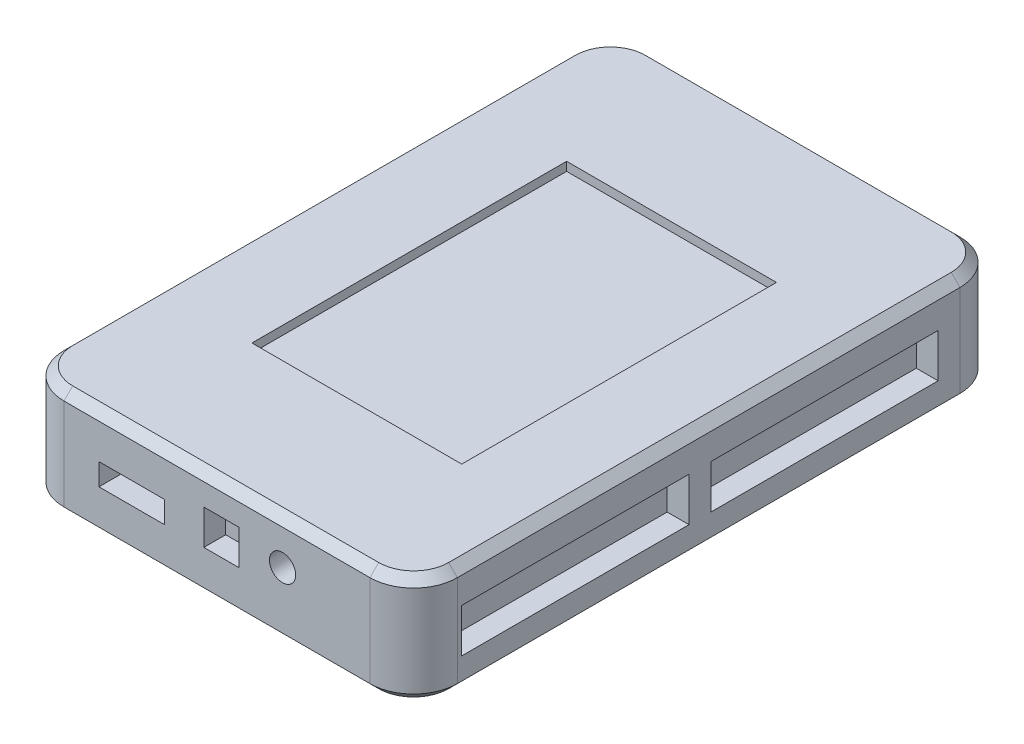
SolidWorks part; units mm, degrees
ref_plane "Front Plane" through (0, 0, 0) normal (0, 0, 1) x (1, 0, 0)
ref_plane "Top Plane" through (0, 0, 0) normal (0, 1, 0) x (1, 0, 0)
ref_plane "Right Plane" through (0, 0, 0) normal (1, 0, 0) x (0, 0, -1)
sketch "Esquisse1" plane through (0, 0, 0) normal (0, 1, 0) x (1, 0, 0)
  line L1 (0, 0) -> (90, 0)
  line L2 (0, 0) -> (0, 135)
  line L3 (0, 135) -> (90, 135)
  line L4 (90, 0) -> (90, 135)
  dimension "D1" = 90
  dimension "D2" = 135
extrude "Boss.-Extru.1" add sketch "Esquisse1" along normal blind 25 contours L3 L4 L1 L2
fillet "Congé1" radius 10 1 edges at (90, 12.5, 0)
fillet "Congé2" radius 10 1 edges at (90, 12.5, -135)
fillet "Congé3" radius 10 1 edges at (0, 12.5, -135)
fillet "Congé4" radius 10 1 edges at (0, 12.5, 0)
chamfer "Chanfrein1" distance 2 angle 45 8 edges at (45, 25, 0) (2.9289, 25, -2.9289) (87.0711, 25, -2.9289) (0, 25, -67.5) (90, 25, -67.5) (2.9289, 25, -132.0711) (87.0711, 25, -132.0711) (45, 25, -135)
chamfer "Chanfrein2" distance 2 angle 45 8 edges at (87.0711, 0, -2.9289) (90, 0, -67.5) (87.0711, 0, -132.0711) (45, 0, -135) (2.9289, 0, -132.0711) (0, 0, -67.5) (2.9289, 0, -2.9289) (45, 0, 0)
ref_plane "Plan1" through (0, 0, 0) normal (0, 0, 1) x (1, 0, 0)
sketch "Esquisse2" plane through (0, 0, 0) normal (0, 0, 1) x (1, 0, 0)
  line L1 (42, 18) -> (50, 18)
  line L2 (42, 18) -> (42, 10)
  line L3 (42, 10) -> (50, 10)
  line L4 (50, 18) -> (50, 10)
  line L5 (18, 15) -> (33, 15)
  line L6 (18, 15) -> (18, 10)
  line L7 (18, 10) -> (33, 10)
  line L8 (33, 15) -> (33, 10)
  line L9 (10, 25) -> (80, 25) construction
  line L10 (0, 2) -> (0, 23) construction
  line L11 (90, 23) -> (90, 2) construction
  circle A0 centre (60, 15) radius 3
  dimension "D1" = 6
  dimension "D4" = 10
  dimension "D5" = 15
  dimension "D9" = 30
  dimension "D2" = 8
  dimension "D3" = 8
  dimension "D6" = 5
  dimension "D7" = 10
  dimension "D8" = 18
  dimension "D10" = 7
  dimension "D11" = 40
extrude "Enlèv. mat.-Extru.1" cut sketch "Esquisse2" against normal blind 5
ref_plane "Plan2" through (0, 0, 0) normal (-1, 0, 0) x (0, 0, 1)
sketch "Esquisse3" plane through (0, 0, 0) normal (-1, 0, 0) x (0, 0, 1)
  line L0 (-125, 25) -> (-10, 25) construction
  line L1 (-90, 17) -> (-15, 17)
  line L2 (-90, 17) -> (-90, 9)
  line L3 (-90, 9) -> (-15, 9)
  line L4 (-15, 17) -> (-15, 9)
  line L5 (0, -11.55) -> (0, 11.55) construction
  line L6 (-135, 2) -> (-135, 23) construction
  circle A0 centre (-112, 17) radius 2
  circle A1 centre (-100, 17) radius 2
  point P10 (-67.5, 25)
  dimension "D1" = 4
  dimension "D2" = 4
  dimension "D5" = 8
  dimension "D6" = 8
  dimension "D9" = 23
  dimension "D10" = 35
  dimension "D3" = 75
  dimension "D4" = 8
  dimension "D7" = 8
  dimension "D8" = 15
extrude "Enlèv. mat.-Extru.2" cut sketch "Esquisse3" against normal blind 5
ref_plane "Plan3" through (0, 25, 0) normal (0, 1, 0) x (1, 0, 0)
sketch "Esquisse4" plane through (0, 25, 0) normal (0, 1, 0) x (1, 0, 0)
  line L0 (10, 135) -> (80, 135) construction
  line L1 (70, 31) -> (22, 31)
  line L2 (70, 31) -> (70, 103)
  line L3 (70, 103) -> (22, 103)
  line L4 (22, 31) -> (22, 103)
  line L5 (0, 10) -> (0, 125) construction
  dimension "D1" = 48
  dimension "D2" = 72
  dimension "D3" = 32
  dimension "D4" = 22
extrude "Enlèv. mat.-Extru.3" cut sketch "Esquisse4" against normal blind 2 contours L1 L4 L3 L2
ref_plane "Plan4" through (0, 0, -135) normal (0, 0, -1) x (-1, 0, 0)
sketch "Esquisse5" plane through (0, 0, -135) normal (0, 0, -1) x (-1, 0, 0)
  line L0 (-30, 20) -> (-20, 20)
  line L1 (-30, 10) -> (-20, 10)
  line L2 (-80, 25) -> (-10, 25) construction
  line L3 (0, 23) -> (0, 2) construction
  arc A0 (-20, 20) -> (-20, 10) centre (-20, 15) cw
  arc A1 (-30, 10) -> (-30, 20) centre (-30, 15) cw
  point P8 (-35, 15)
  point P9 (-15, 15)
  dimension "D1" = 10
  dimension "D2" = 5
  dimension "D3" = 20
  dimension "D4" = 15
extrude "Enlèv. mat.-Extru.4" cut sketch "Esquisse5" against normal blind 2
ref_plane "Plan5" through (0, 0, -133) normal (0, 0, -1) x (-1, 0, 0)
sketch "Esquisse6" plane through (0, 0, -133) normal (0, 0, -1) x (-1, 0, 0)
  line L0 (-20, 20) -> (-30, 20) construction
  circle A0 centre (-30, 15) radius 1.5
  circle A1 centre (-20, 15) radius 1.5
  arc A2 (-20, 10) -> (-20, 20) centre (-20, 15) ccw construction
  point P8 (-15, 15)
  dimension "D1" = 3
  dimension "D2" = 3
  dimension "D3" = 5
  dimension "D4" = 5
extrude "Boss.-Extru.2" add sketch "Esquisse6" along normal blind 2
ref_plane "Plan6" through (90, 0, 0) normal (1, 0, 0) x (0, 0, -1)
sketch "Esquisse7" plane through (90, 0, 0) normal (1, 0, 0) x (0, 0, -1)
  line L0 (10, 25) -> (125, 25) construction
  line L1 (11, 17) -> (63, 17)
  line L2 (11, 17) -> (11, 7)
  line L3 (11, 7) -> (63, 7)
  line L4 (63, 17) -> (63, 7)
  line L5 (68, 17) -> (120, 17)
  line L6 (68, 17) -> (68, 7)
  line L7 (68, 7) -> (120, 7)
  line L8 (120, 17) -> (120, 7)
  line L9 (0, 2) -> (0, 23) construction
  line L10 (135, 23) -> (135, 2) construction
  point P12 (0, 12.5)
  dimension "D1" = 52
  dimension "D2" = 10
  dimension "D3" = 52
  dimension "D4" = 10
  dimension "D5" = 8
  dimension "D6" = 11
  dimension "D7" = 15
  dimension "D8" = 8
extrude "Enlèv. mat.-Extru.5" cut sketch "Esquisse7" against normal blind 5
